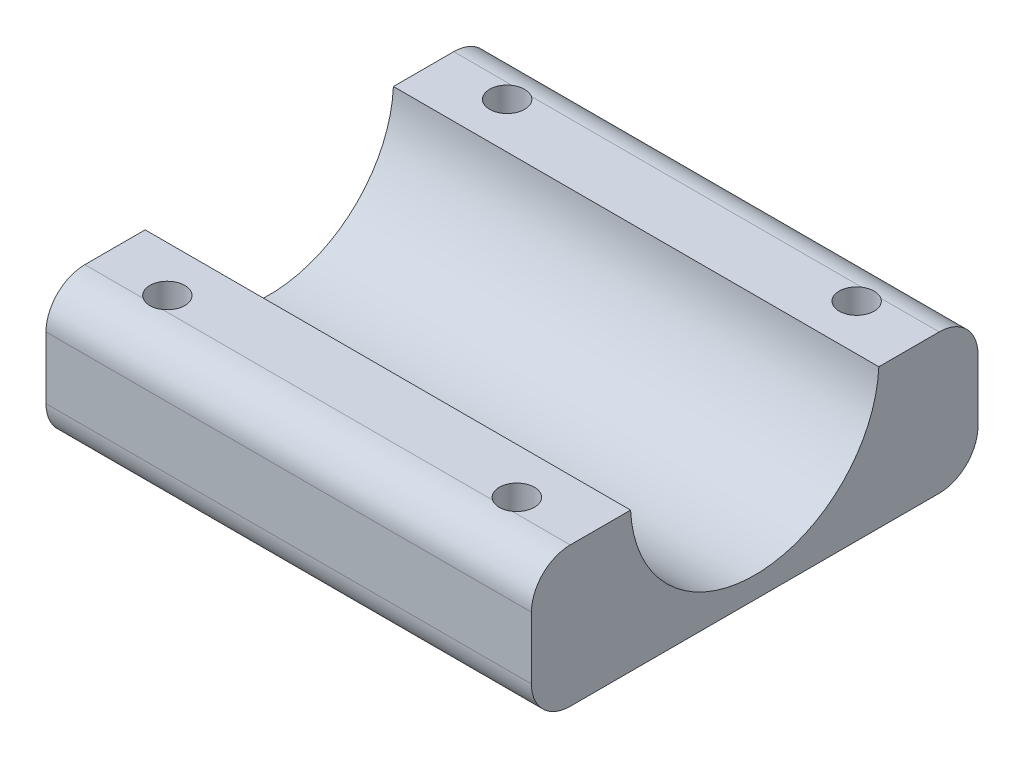
SolidWorks part; units mm, degrees
ref_plane "Front Plane" through (0, 0, 0) normal (0, 0, 1) x (1, 0, 0)
ref_plane "Top Plane" through (0, 0, 0) normal (0, 1, 0) x (1, 0, 0)
ref_plane "Right Plane" through (0, 0, 0) normal (1, 0, 0) x (0, 0, -1)
sketch "Sketch1" plane through (0, 0, 0) normal (1, 0, 0) x (0, 0, -1)
  line L0 (-19, -15) -> (19, -15)
  line L1 (23, -11) -> (23, -4.6)
  line L2 (19, -0.6) -> (-19, -0.6)
  line L3 (-23, -4.6) -> (-23, -11)
  arc A0 (19, -15) -> (23, -11) centre (19, -11) ccw
  arc A1 (23, -4.6) -> (19, -0.6) centre (19, -4.6) ccw
  arc A2 (-19, -0.6) -> (-23, -4.6) centre (-19, -4.6) ccw
  arc A3 (-23, -11) -> (-19, -15) centre (-19, -11) ccw
extrude "Boss-Extrude1" add sketch "Sketch1" along normal mid plane 50
sketch "Sketch2" plane through (0, 0, 0) normal (1, 0, 0) x (0, 0, -1)
  circle A0 centre (0, 0) radius 12.8
extrude "Cut-Extrude1" cut sketch "Sketch2" against normal through all and the other way through all
ref_plane "Plane1" through (0, -15, 0) normal (0, 1, 0) x (1, 0, 0)
sketch "Sketch3" plane through (0, -15, 0) normal (0, 1, 0) x (1, 0, 0)
  circle A0 centre (18, -17.5) radius 1.8
  circle A1 centre (18, 17.5) radius 1.8
  circle A2 centre (-18, -17.5) radius 1.8
  circle A3 centre (-18, 17.5) radius 1.8
extrude "Cut-Extrude2" cut sketch "Sketch3" along normal blind 16
ref_plane "Plane2" through (0, -15, 0) normal (0, 1, 0) x (1, 0, 0)
sketch "Sketch4" plane through (0, -15, 0) normal (0, 1, 0) x (1, 0, 0)
  circle A0 centre (18, -17.5) radius 3.25
  circle A1 centre (18, 17.5) radius 3.25
  circle A2 centre (-18, -17.5) radius 3.25
  circle A3 centre (-18, 17.5) radius 3.25
extrude "Cut-Extrude3" cut sketch "Sketch4" along normal blind 5.6
